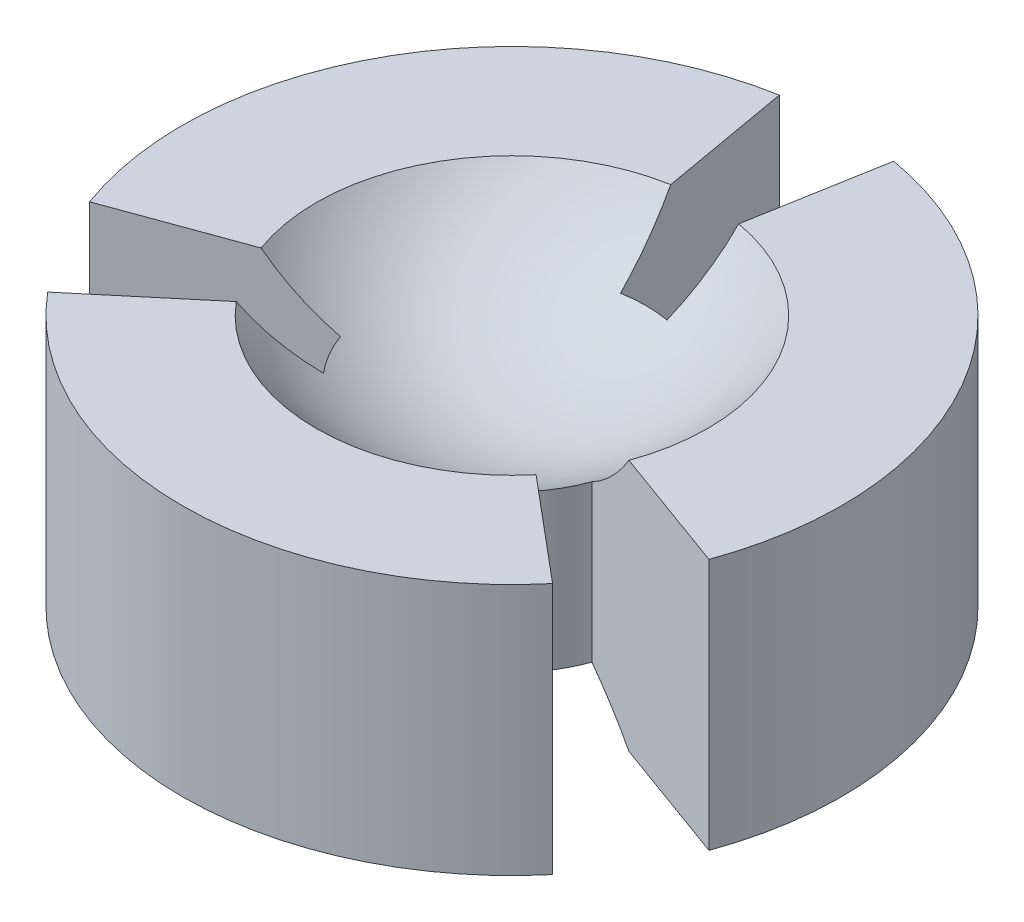
SolidWorks part; units mm, degrees
ref_plane "前视基准面" through (0, 0, 0) normal (0, 0, 1) x (1, 0, 0)
ref_plane "上视基准面" through (0, 0, 0) normal (0, 1, 0) x (1, 0, 0)
ref_plane "右视基准面" through (0, 0, 0) normal (1, 0, 0) x (0, 0, -1)
sketch "草图1" plane through (0, 0, 0) normal (0, 0, 1) x (1, 0, 0)
  line L17 (0, 0) -> (0, 8.1) construction
  line L18 (0, 3.6) -> (-3.6, 3.6) construction
  line L19 (0, 3.6) -> (-3.1177, 5.4) construction
  line L20 (-3.1177, 5.4) -> (0, 5.4) construction
  line L23 (0, 5.6) -> (-2.925, 5.6) construction
  line L24 (0, 8.1) -> (0, 11.55) construction
  line L25 (-2.925, 5.6) -> (-4.925, 5.6)
  line L26 (-4.925, 5.6) -> (-4.925, 9.3667)
  line L27 (-2.925, 9.3667) -> (-4.925, 9.3667)
  line L28 (0, 7.9) -> (0, 6.6)
  circle A11 centre (0, 11.55) radius 3.45 construction
  arc A12 (-3.1177, 5.4) -> (0, 0) centre (0, 3.6) ccw construction
  arc A14 (-2.925, 9.3667) -> (0, 7.9) centre (0, 11.55) ccw
  arc A15 (-2.925, 5.6) -> (0, 6.6) centre (0, 1.8221) cw
  point P2 (0, 3.6)
  point P17 (0, 6.6)
  dimension "D1" = 8.1
  dimension "D4" = 0.2
  dimension "D3" = 30
  dimension "D8" = 2
  dimension "D7" = 0.2
  dimension "D2" = 3.6
  dimension "D5" = 3.45
  dimension "D6" = 2
  dimension "D9" = 1
revolve "旋转2" add sketch "草图1" angle 360 about L28
sketch "草图2" plane through (0, 9.3667, 0) normal (0, 1, 0) x (1, 0, 0)
  line L0 (0, 0) -> (0, 2) construction
  line L3 (-0.3473, 1.9696) -> (-1.7365, 9.8481)
  line L4 (0.3473, 1.9696) -> (1.7365, 9.8481)
  line L5 (1.8794, -0.684) -> (9.3969, -3.4202)
  line L6 (1.5321, -1.2856) -> (7.6604, -6.4279)
  line L7 (0, 0) -> (1.7321, -1) construction
  line L8 (-1.5321, -1.2856) -> (-7.6604, -6.4279)
  line L9 (-1.8794, -0.684) -> (-9.3969, -3.4202)
  line L10 (0, 0) -> (-1.7321, -1) construction
  arc A2 (1.7365, 9.8481) -> (-1.7365, 9.8481) centre (0, 0) ccw
  arc A3 (0.3473, 1.9696) -> (-0.3473, 1.9696) centre (0, 0) ccw
  arc A4 (7.6604, -6.4279) -> (9.3969, -3.4202) centre (0, 0) ccw
  arc A5 (1.5321, -1.2856) -> (1.8794, -0.684) centre (0, 0) ccw
  arc A6 (-9.3969, -3.4202) -> (-7.6604, -6.4279) centre (0, 0) ccw
  arc A7 (-1.8794, -0.684) -> (-1.5321, -1.2856) centre (0, 0) ccw
  point P19 (0, 0)
  dimension "D1" = 10
  dimension "D2" = 10
  dimension "D4" = 10
  dimension "D3" = 3
extrude "切除-拉伸1" cut sketch "草图2" against normal through all
